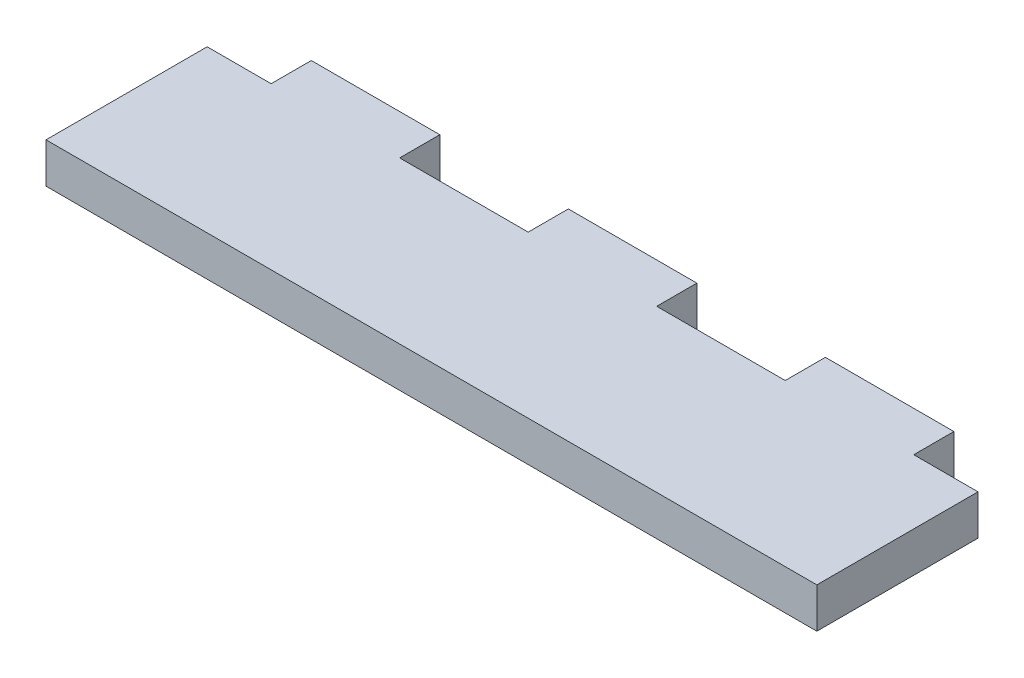
SolidWorks part; units mm, degrees
ref_plane "Front Plane" through (0, 0, 0) normal (0, 0, 1) x (1, 0, 0)
ref_plane "Top Plane" through (0, 0, 0) normal (0, 1, 0) x (1, 0, 0)
ref_plane "Right Plane" through (0, 0, 0) normal (1, 0, 0) x (0, 0, -1)
sketch "Sketch1" plane through (0, 0, 0) normal (0, 1, 0) x (1, 0, 0)
  line L0 (38.1, -41.275) -> (48.26, -41.275)
  line L1 (76.2, -41.275) -> (-76.2, -41.275)
  line L2 (76.2, -41.275) -> (76.2, 41.275)
  line L3 (76.2, 41.275) -> (-76.2, 41.275)
  line L4 (-76.2, -41.275) -> (-76.2, 41.275)
  line L5 (76.2, -41.275) -> (-76.2, 41.275) construction
  line L6 (76.2, 41.275) -> (-76.2, -41.275) construction
  line L7 (58.42, -41.275) -> (68.58, -41.275)
  line L8 (58.42, -41.275) -> (58.42, -44.45)
  line L9 (58.42, -44.45) -> (68.58, -44.45)
  line L10 (68.58, -41.275) -> (68.58, -44.45)
  line L11 (38.1, -41.275) -> (38.1, -44.45)
  line L12 (38.1, -44.45) -> (48.26, -44.45)
  line L13 (48.26, -41.275) -> (48.26, -44.45)
  line L14 (17.78, -41.275) -> (27.94, -41.275)
  line L15 (17.78, -41.275) -> (17.78, -44.45)
  line L16 (17.78, -44.45) -> (27.94, -44.45)
  line L17 (27.94, -41.275) -> (27.94, -44.45)
  line L18 (58.42, 44.45) -> (68.58, 44.45)
  line L19 (58.42, 44.45) -> (58.42, 41.275)
  line L20 (58.42, 41.275) -> (68.58, 41.275)
  line L21 (68.58, 44.45) -> (68.58, 41.275)
  line L22 (38.1, 44.45) -> (48.26, 44.45)
  line L23 (38.1, 44.45) -> (38.1, 41.275)
  line L24 (38.1, 41.275) -> (48.26, 41.275)
  line L25 (48.26, 44.45) -> (48.26, 41.275)
  line L26 (17.78, 44.45) -> (27.94, 44.45)
  line L27 (17.78, 44.45) -> (17.78, 41.275)
  line L28 (17.78, 41.275) -> (27.94, 41.275)
  line L29 (27.94, 44.45) -> (27.94, 41.275)
  line L30 (58.42, -41.275) -> (38.1, -41.275) construction
  circle A0 centre (-65.0766, 0) radius 7.747
  point P0 (0, 0)
  dimension "D9" = 15.494
  dimension "D1" = 3.175
  dimension "D2" = 10.16
  dimension "D5" = 20.32
  dimension "D6" = 82.55
  dimension "D7" = 152.4
  dimension "D8" = 7.62
  dimension "D3" = 3
  dimension "D4" = 2
extrude "Main Extrude" add sketch "Sketch1" along normal blind 3.175 contours L17 L1 L15 L16 | L4 L1 L0 L2 L3 | L13 L0 L11 L12 | L29 L26 L27 L3 | L10 L9 L8 L7 | L18 L21 L20 L19 | L22 L25 L24 L23
sketch "Sketch2" plane through (0, 3.175, 0) normal (0, 1, 0) x (1, 0, 0)
  line L0 (-47.3754, 15.24) -> (-47.3754, -15.24) construction
  line L1 (-47.3754, 0) -> (-76.2, 0) construction
  line L2 (-76.2, -41.275) -> (-76.2, 41.275) construction
  circle A0 centre (-47.3754, 15.24) radius 2.54
  circle A1 centre (-23.4994, 15.24) radius 2.54
  circle A2 centre (-23.4994, -15.24) radius 2.54
  circle A3 centre (-47.3754, -15.24) radius 2.54
  dimension "D4" = 23.876
  dimension "D5" = 5.08
  dimension "D3" = 30.48
  dimension "D1" = 2
  dimension "D2" = 2
extrude "Caster Mounting Holes" cut sketch "Sketch2" against normal through all
sketch "Sketch3" plane through (0, 3.175, 0) normal (0, 1, 0) x (1, 0, 0)
  line L0 (76.2, -41.275) -> (76.2, 41.275) construction
  line L1 (73.66, 41.275) -> (76.2, 41.275)
  line L2 (73.66, 41.275) -> (73.66, -41.275)
  line L3 (73.66, -41.275) -> (76.2, -41.275)
  line L4 (76.2, 41.275) -> (76.2, -41.275)
  dimension "D1" = 2.54
extrude "Remove Uneven Back Edge" cut sketch "Sketch3" against normal through all
sketch "Sketch4" plane through (0, 3.175, 0) normal (0, 1, 0) x (1, 0, 0)
  line L0 (12.7224, 54.0071) -> (12.7224, 28.5343)
  line L1 (12.7224, 28.5343) -> (84.7183, 28.5343)
  line L2 (84.7183, 28.5343) -> (84.7183, -50.0411)
  line L3 (84.7183, -50.0411) -> (-114.7311, -51.9376)
  line L4 (-114.7311, -51.9376) -> (-115.7385, 54.0071)
  line L5 (-115.7385, 54.0071) -> (12.7224, 54.0071)
extrude "Cut-Extrude2" cut sketch "Sketch4" against normal through all
sketch "Sketch5" plane through (0, 3.175, 0) normal (0, 1, 0) x (1, 0, 0)
  line L152 (12.6462, 41.3512) -> (12.6462, 28.4581)
  line L153 (12.6462, 28.4581) -> (73.7362, 28.4581)
  line L154 (73.7362, 28.4581) -> (73.7362, 41.3512)
  line L155 (73.7362, 41.3512) -> (68.6562, 41.3512)
  line L156 (68.6562, 41.3512) -> (68.6562, 44.5262)
  line L157 (68.6562, 44.5262) -> (58.3438, 44.5262)
  line L158 (58.3438, 44.5262) -> (58.3438, 41.3512)
  line L159 (58.3438, 41.3512) -> (48.3362, 41.3512)
  line L160 (48.3362, 41.3512) -> (48.3362, 44.5262)
  line L161 (48.3362, 44.5262) -> (38.0238, 44.5262)
  line L162 (38.0238, 44.5262) -> (38.0238, 41.3512)
  line L163 (38.0238, 41.3512) -> (28.0162, 41.3512)
  line L164 (28.0162, 41.3512) -> (28.0162, 44.5262)
  line L165 (28.0162, 44.5262) -> (17.7038, 44.5262)
  line L166 (17.7038, 44.5262) -> (17.7038, 41.3512)
  line L167 (17.7038, 41.3512) -> (12.6462, 41.3512)
  line L168 (12.6462, 41.3512) -> (12.6462, 28.4581)
  line L169 (12.6462, 28.4581) -> (73.7362, 28.4581)
  line L170 (73.7362, 28.4581) -> (73.7362, 41.3512)
  line L171 (73.7362, 41.3512) -> (68.6562, 41.3512)
  line L172 (68.6562, 41.3512) -> (68.6562, 44.5262)
  line L173 (68.6562, 44.5262) -> (58.3438, 44.5262)
  line L174 (58.3438, 44.5262) -> (58.3438, 41.3512)
  line L175 (58.3438, 41.3512) -> (48.3362, 41.3512)
  line L176 (48.3362, 41.3512) -> (48.3362, 44.5262)
  line L177 (48.3362, 44.5262) -> (38.0238, 44.5262)
  line L178 (38.0238, 44.5262) -> (38.0238, 41.3512)
  line L179 (38.0238, 41.3512) -> (28.0162, 41.3512)
  line L180 (28.0162, 41.3512) -> (28.0162, 44.5262)
  line L181 (28.0162, 44.5262) -> (17.7038, 44.5262)
  line L182 (17.7038, 44.5262) -> (17.7038, 41.3512)
  line L183 (17.7038, 41.3512) -> (12.6462, 41.3512)
  dimension "D1" = 0.0762
